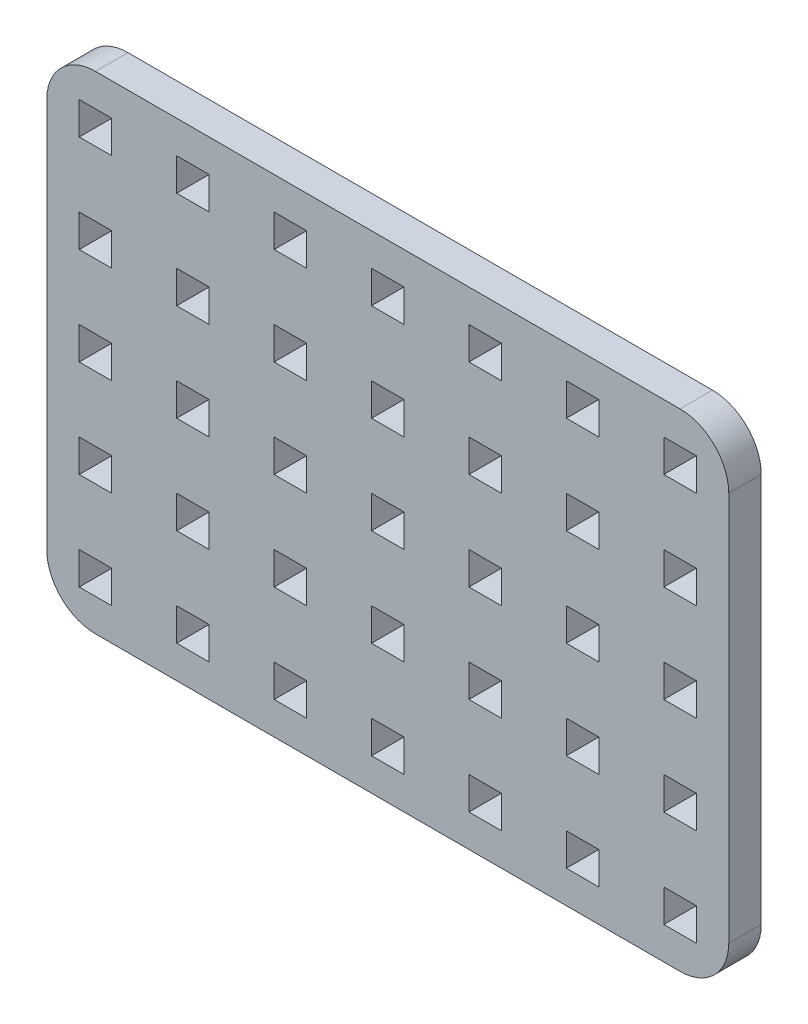
SolidWorks part; units mm, degrees
ref_plane "Alzado" through (0, 0, 0) normal (0, 0, 1) x (1, 0, 0)
ref_plane "Planta" through (0, 0, 0) normal (0, 1, 0) x (1, 0, 0)
ref_plane "Vista lateral" through (0, 0, 0) normal (1, 0, 0) x (0, 0, -1)
sketch "Model" plane through (0, 0, 0) normal (0, 0, 1) x (1, 0, 0)
  line L0 (7.8859, 295.5496) -> (7.8859, 292.5496)
  line L1 (10.8859, 295.5496) -> (7.8859, 295.5496)
  line L2 (10.8859, 292.5496) -> (10.8859, 295.5496)
  line L3 (7.8859, 292.5496) -> (10.8859, 292.5496)
  line L4 (16.8859, 295.5496) -> (16.8859, 292.5496)
  line L5 (19.8859, 295.5496) -> (16.8859, 295.5496)
  line L6 (19.8859, 292.5496) -> (19.8859, 295.5496)
  line L7 (16.8859, 292.5496) -> (19.8859, 292.5496)
  line L8 (25.8859, 295.5496) -> (25.8859, 292.5496)
  line L9 (28.8859, 295.5496) -> (25.8859, 295.5496)
  line L10 (28.8859, 292.5496) -> (28.8859, 295.5496)
  line L11 (25.8859, 292.5496) -> (28.8859, 292.5496)
  line L12 (52.8859, 295.5496) -> (52.8859, 292.5496)
  line L13 (55.8859, 295.5496) -> (52.8859, 295.5496)
  line L14 (55.8859, 292.5496) -> (55.8859, 295.5496)
  line L15 (52.8859, 292.5496) -> (55.8859, 292.5496)
  line L16 (61.8859, 295.5496) -> (61.8859, 292.5496)
  line L17 (64.8859, 295.5496) -> (61.8859, 295.5496)
  line L18 (64.8859, 292.5496) -> (64.8859, 295.5496)
  line L19 (61.8859, 292.5496) -> (64.8859, 292.5496)
  line L20 (7.8859, 259.5496) -> (7.8859, 256.5496)
  line L21 (10.8859, 259.5496) -> (7.8859, 259.5496)
  line L22 (10.8859, 256.5496) -> (10.8859, 259.5496)
  line L23 (7.8859, 256.5496) -> (10.8859, 256.5496)
  line L24 (16.8859, 259.5496) -> (16.8859, 256.5496)
  line L25 (19.8859, 259.5496) -> (16.8859, 259.5496)
  line L26 (19.8859, 256.5496) -> (19.8859, 259.5496)
  line L27 (16.8859, 256.5496) -> (19.8859, 256.5496)
  line L28 (25.8859, 259.5496) -> (25.8859, 256.5496)
  line L29 (28.8859, 259.5496) -> (25.8859, 259.5496)
  line L30 (28.8859, 256.5496) -> (28.8859, 259.5496)
  line L31 (25.8859, 256.5496) -> (28.8859, 256.5496)
  line L32 (52.8859, 259.5496) -> (52.8859, 256.5496)
  line L33 (55.8859, 259.5496) -> (52.8859, 259.5496)
  line L34 (55.8859, 256.5496) -> (55.8859, 259.5496)
  line L35 (52.8859, 256.5496) -> (55.8859, 256.5496)
  line L36 (61.8859, 259.5496) -> (61.8859, 256.5496)
  line L37 (64.8859, 259.5496) -> (61.8859, 259.5496)
  line L38 (64.8859, 256.5496) -> (64.8859, 259.5496)
  line L39 (61.8859, 256.5496) -> (64.8859, 256.5496)
  line L40 (7.8859, 268.5496) -> (7.8859, 265.5496)
  line L41 (10.8859, 268.5496) -> (7.8859, 268.5496)
  line L42 (10.8859, 265.5496) -> (10.8859, 268.5496)
  line L43 (7.8859, 265.5496) -> (10.8859, 265.5496)
  line L44 (16.8859, 268.5496) -> (16.8859, 265.5496)
  line L45 (19.8859, 268.5496) -> (16.8859, 268.5496)
  line L46 (19.8859, 265.5496) -> (19.8859, 268.5496)
  line L47 (16.8859, 265.5496) -> (19.8859, 265.5496)
  line L48 (25.8859, 268.5496) -> (25.8859, 265.5496)
  line L49 (28.8859, 268.5496) -> (25.8859, 268.5496)
  line L50 (28.8859, 265.5496) -> (28.8859, 268.5496)
  line L51 (25.8859, 265.5496) -> (28.8859, 265.5496)
  line L52 (52.8859, 268.5496) -> (52.8859, 265.5496)
  line L53 (55.8859, 268.5496) -> (52.8859, 268.5496)
  line L54 (55.8859, 265.5496) -> (55.8859, 268.5496)
  line L55 (52.8859, 265.5496) -> (55.8859, 265.5496)
  line L56 (61.8859, 268.5496) -> (61.8859, 265.5496)
  line L57 (64.8859, 268.5496) -> (61.8859, 268.5496)
  line L58 (64.8859, 265.5496) -> (64.8859, 268.5496)
  line L59 (61.8859, 265.5496) -> (64.8859, 265.5496)
  line L60 (34.8859, 295.5496) -> (34.8859, 292.5496)
  line L61 (37.8859, 295.5496) -> (34.8859, 295.5496)
  line L62 (37.8859, 292.5496) -> (37.8859, 295.5496)
  line L63 (34.8859, 292.5496) -> (37.8859, 292.5496)
  line L64 (43.8859, 295.5496) -> (43.8859, 292.5496)
  line L65 (46.8859, 295.5496) -> (43.8859, 295.5496)
  line L66 (46.8859, 292.5496) -> (46.8859, 295.5496)
  line L67 (43.8859, 292.5496) -> (46.8859, 292.5496)
  line L68 (34.8859, 259.5496) -> (34.8859, 256.5496)
  line L69 (37.8859, 259.5496) -> (34.8859, 259.5496)
  line L70 (37.8859, 256.5496) -> (37.8859, 259.5496)
  line L71 (34.8859, 256.5496) -> (37.8859, 256.5496)
  line L72 (43.8859, 259.5496) -> (43.8859, 256.5496)
  line L73 (46.8859, 259.5496) -> (43.8859, 259.5496)
  line L74 (46.8859, 256.5496) -> (46.8859, 259.5496)
  line L75 (43.8859, 256.5496) -> (46.8859, 256.5496)
  line L76 (34.8859, 268.5496) -> (34.8859, 265.5496)
  line L77 (37.8859, 268.5496) -> (34.8859, 268.5496)
  line L78 (37.8859, 265.5496) -> (37.8859, 268.5496)
  line L79 (34.8859, 265.5496) -> (37.8859, 265.5496)
  line L80 (43.8859, 268.5496) -> (43.8859, 265.5496)
  line L81 (46.8859, 268.5496) -> (43.8859, 268.5496)
  line L82 (46.8859, 265.5496) -> (46.8859, 268.5496)
  line L83 (43.8859, 265.5496) -> (46.8859, 265.5496)
  line L84 (7.8859, 277.5496) -> (7.8859, 274.5496)
  line L85 (10.8859, 277.5496) -> (7.8859, 277.5496)
  line L86 (10.8859, 274.5496) -> (10.8859, 277.5496)
  line L87 (7.8859, 274.5496) -> (10.8859, 274.5496)
  line L88 (16.8859, 277.5496) -> (16.8859, 274.5496)
  line L89 (19.8859, 277.5496) -> (16.8859, 277.5496)
  line L90 (19.8859, 274.5496) -> (19.8859, 277.5496)
  line L91 (16.8859, 274.5496) -> (19.8859, 274.5496)
  line L92 (25.8859, 277.5496) -> (25.8859, 274.5496)
  line L93 (28.8859, 277.5496) -> (25.8859, 277.5496)
  line L94 (28.8859, 274.5496) -> (28.8859, 277.5496)
  line L95 (25.8859, 274.5496) -> (28.8859, 274.5496)
  line L96 (52.8859, 277.5496) -> (52.8859, 274.5496)
  line L97 (55.8859, 277.5496) -> (52.8859, 277.5496)
  line L98 (55.8859, 274.5496) -> (55.8859, 277.5496)
  line L99 (52.8859, 274.5496) -> (55.8859, 274.5496)
  line L100 (61.8859, 277.5496) -> (61.8859, 274.5496)
  line L101 (64.8859, 277.5496) -> (61.8859, 277.5496)
  line L102 (64.8859, 274.5496) -> (64.8859, 277.5496)
  line L103 (61.8859, 274.5496) -> (64.8859, 274.5496)
  line L104 (7.8859, 286.5496) -> (7.8859, 283.5496)
  line L105 (10.8859, 286.5496) -> (7.8859, 286.5496)
  line L106 (10.8859, 283.5496) -> (10.8859, 286.5496)
  line L107 (7.8859, 283.5496) -> (10.8859, 283.5496)
  line L108 (16.8859, 286.5496) -> (16.8859, 283.5496)
  line L109 (19.8859, 286.5496) -> (16.8859, 286.5496)
  line L110 (19.8859, 283.5496) -> (19.8859, 286.5496)
  line L111 (16.8859, 283.5496) -> (19.8859, 283.5496)
  line L112 (25.8859, 286.5496) -> (25.8859, 283.5496)
  line L113 (28.8859, 286.5496) -> (25.8859, 286.5496)
  line L114 (28.8859, 283.5496) -> (28.8859, 286.5496)
  line L115 (25.8859, 283.5496) -> (28.8859, 283.5496)
  line L116 (52.8859, 286.5496) -> (52.8859, 283.5496)
  line L117 (55.8859, 286.5496) -> (52.8859, 286.5496)
  line L118 (55.8859, 283.5496) -> (55.8859, 286.5496)
  line L119 (52.8859, 283.5496) -> (55.8859, 283.5496)
  line L120 (61.8859, 286.5496) -> (61.8859, 283.5496)
  line L121 (64.8859, 286.5496) -> (61.8859, 286.5496)
  line L122 (64.8859, 283.5496) -> (64.8859, 286.5496)
  line L123 (61.8859, 283.5496) -> (64.8859, 283.5496)
  line L124 (34.8859, 277.5496) -> (34.8859, 274.5496)
  line L125 (37.8859, 277.5496) -> (34.8859, 277.5496)
  line L126 (37.8859, 274.5496) -> (37.8859, 277.5496)
  line L127 (34.8859, 274.5496) -> (37.8859, 274.5496)
  line L128 (43.8859, 277.5496) -> (43.8859, 274.5496)
  line L129 (46.8859, 277.5496) -> (43.8859, 277.5496)
  line L130 (46.8859, 274.5496) -> (46.8859, 277.5496)
  line L131 (43.8859, 274.5496) -> (46.8859, 274.5496)
  line L132 (34.8859, 286.5496) -> (34.8859, 283.5496)
  line L133 (37.8859, 286.5496) -> (34.8859, 286.5496)
  line L134 (37.8859, 283.5496) -> (37.8859, 286.5496)
  line L135 (34.8859, 283.5496) -> (37.8859, 283.5496)
  line L136 (43.8859, 286.5496) -> (43.8859, 283.5496)
  line L137 (46.8859, 286.5496) -> (43.8859, 286.5496)
  line L138 (46.8859, 283.5496) -> (46.8859, 286.5496)
  line L139 (43.8859, 283.5496) -> (46.8859, 283.5496)
  line L140 (9.3859, 298.5496) -> (63.3859, 298.5496)
  line L141 (9.3859, 253.5496) -> (63.3859, 253.5496)
  line L142 (4.8859, 294.0496) -> (4.8859, 258.0496)
  line L143 (67.8859, 294.0496) -> (67.8859, 258.0496)
  arc A0 (67.8859, 294.0496) -> (63.3859, 298.5496) centre (63.3859, 294.0496) ccw
  arc A1 (63.3859, 253.5496) -> (67.8859, 258.0496) centre (63.3859, 258.0496) ccw
  arc A2 (9.3859, 298.5496) -> (4.8859, 294.0496) centre (9.3859, 294.0496) ccw
  arc A3 (4.8859, 258.0496) -> (9.3859, 253.5496) centre (9.3859, 258.0496) ccw
extrude "Saliente-Extruir1" add sketch "Model" along normal blind 3
